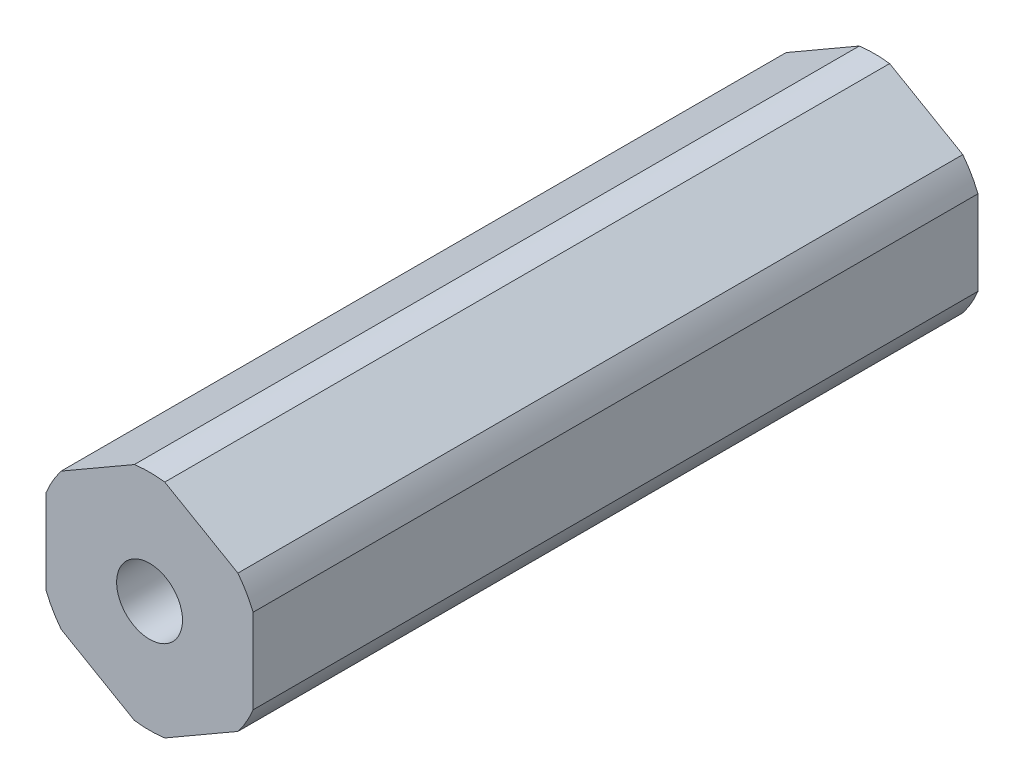
SolidWorks part; units mm, degrees
material "6061-T6 (SS)"
ref_plane "Front Plane" through (0, 0, 0) normal (0, 0, 1) x (1, 0, 0)
ref_plane "Top Plane" through (0, 0, 0) normal (0, 1, 0) x (1, 0, 0)
ref_plane "Right Plane" through (0, 0, 0) normal (1, 0, 0) x (0, 0, -1)
sketch "Sketch1" plane through (0, 0, 0) normal (0, 0, 1) x (1, 0, 0)
  line L1 (0, 7.3323) -> (-6.35, 3.6662)
  line L2 (-6.35, 3.6662) -> (-6.35, -3.6662)
  line L3 (-6.35, -3.6662) -> (0, -7.3323)
  line L4 (0, -7.3323) -> (6.35, -3.6662)
  line L5 (6.35, -3.6662) -> (6.35, 3.6662)
  line L6 (6.35, 3.6662) -> (0, 7.3323)
  circle A0 centre (0, 0) radius 6.858
  circle A1 centre (0, 0) radius 6.35 construction
  dimension "D1" = 12.7
  dimension "D2" = 13.716
extrude "Boss-Extrude1" add sketch "Sketch1" along normal mid plane 44.45 contours L5 A0 L6 L1 L2 L3 L4
sketch "Sketch2" plane through (0, 0, 22.225) normal (0, 0, 1) x (1, 0, 0)
  circle A0 centre (0, 0) radius 2.0193
  dimension "D1" = 4.0386
extrude "Cut-Extrude1" [suppressed] cut sketch "Sketch2" against normal through all
hole_wizard "#10-32 Tapped Hole1" positions "3DSketch2" profile "Sketch4" tap size "#10-32" standard "ANSI Inch"
sketch3d "3DSketch2"
  line L0 (0, 0, 22.225) -> (0, 0, -22.225) construction
  point P0 (0, 0, -22.225)
  point P4 (0, 0, 22.225)
sketch "Sketch4" plane through (0, 0, -22.225) normal (1, 0, 0) x (0, 1, 0)
  line L0 (0, 0) -> (0, 13.1513)
  line L1 (0, 13.1513) -> (2.0193, 11.938)
  line L2 (2.0193, 11.938) -> (2.0193, 0)
  line L5 (2.0193, 0) -> (0, 0)
  line L10 (0, 13.1513) -> (-2.0193, 11.938) construction
  line L11 (0, -6.35) -> (0, 107.95) construction
  dimension "Tap Drill Dia." = 4.0386
  dimension "Tap Drill Depth" = 11.938
  dimension "Drill Angle" = 118
cosmetic thread "Hole Thread1" parameters "D1"=9.652, "D2"=4.826
cosmetic thread "Hole Thread2" parameters "D1"=9.652, "D2"=4.826
